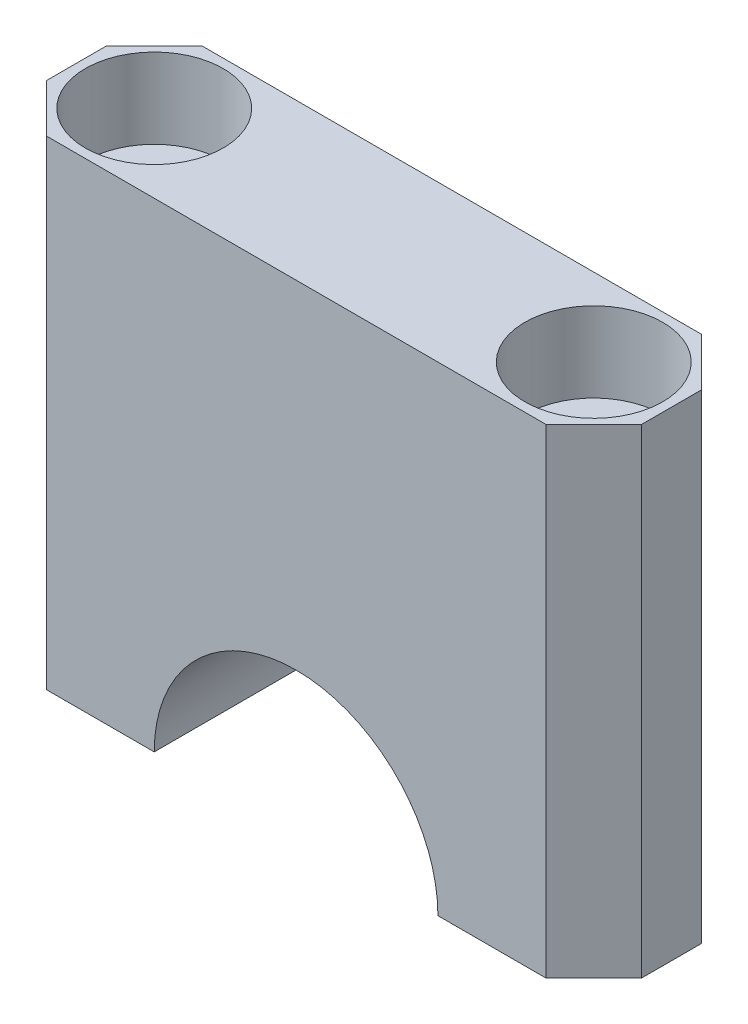
SolidWorks part; units mm, degrees
material "ABS"
ref_plane "Płaszczyzna przednia" through (0, 0, 0) normal (0, 0, 1) x (1, 0, 0)
ref_plane "Płaszczyzna górna" through (0, 0, 0) normal (0, 1, 0) x (1, 0, 0)
ref_plane "Płaszczyzna prawa" through (0, 0, 0) normal (1, 0, 0) x (0, 0, -1)
sketch "Szkic1" plane through (0, 0, 0) normal (0, 1, 0) x (1, 0, 0)
  line L0 (0, -3.9) -> (0, 3.9) construction
  line L1 (12.5, 3.9) -> (-12.5, 3.9)
  line L2 (14.9, 0) -> (-14.9, 0) construction
  line L3 (-14.9, -1.5) -> (-14.9, 1.5)
  line L4 (-14.9, 1.5) -> (-12.5, 3.9)
  line L5 (14.9, 1.5) -> (14.9, -1.5)
  line L6 (14.9, 1.5) -> (12.5, 3.9)
  line L7 (-14.9, -1.5) -> (-12.5, -3.9)
  line L8 (12.5, -3.9) -> (-12.5, -3.9)
  line L9 (14.9, -1.5) -> (12.5, -3.9)
  line L10 (0, 0) -> (-11, 0) construction
  circle A0 centre (-11, 0) radius 2.1
  circle A1 centre (11, 0) radius 2.1
  point P4 (0, 0)
  point P9 (0, 3.9)
  point P12 (0, 0)
  point P15 (-14.9, 0)
  point P18 (14.9, 0)
  dimension "D7" = 4.2
  dimension "D1" = 7.8
  dimension "D2" = 29.8
  dimension "D3" = 3
  dimension "D4" = 25
  dimension "D5" = 3
  dimension "D6" = 11
extrude "Dodanie-wyciągnięcie1" add sketch "Szkic1" against normal blind 24
ref_plane "Płaszczyzna1" through (0, 0, -3.9) normal (0, 0, -1) x (-1, 0, 0)
sketch "Szkic2" plane through (0, 0, -3.9) normal (0, 0, -1) x (-1, 0, 0)
  line L0 (0, 0) -> (0, -24) construction
  line L1 (-12.5, -24) -> (12.5, -24) construction
  line L2 (-7.1, -24) -> (7.1, -24)
  arc A0 (7.1, -24) -> (-7.1, -24) centre (0, -24) ccw
  dimension "D2" = 7.1
  dimension "D1" = 24
extrude "Wytnij-wyciągnięcie1" cut sketch "Szkic2" against normal up to next
sketch "Szkic3" plane through (0, 0, 0) normal (0, 1, 0) x (1, 0, 0)
  line L0 (0, -4.29) -> (0, 4.29) construction
  circle A0 centre (-11, 0) radius 3.45
  circle A1 centre (11, 0) radius 3.45
  dimension "D1" = 6.9
extrude "Wytnij-wyciągnięcie2" cut sketch "Szkic3" against normal blind 4
equation "\"Tolerance\"= 0.1"
equation "\"Depth\"=10"
equation "\"D1@Szkic1\"=\"RailZ\"-\"Tolerance\"*2"
equation "\"Width\"= 16"
equation "\"D2@Szkic1\"=\"Diameter\"+\"RailX\"*2-\"Tolerance\"*2"
equation "\"Diameter\"= 14"
equation "\"RailX\"= 8"
equation "\"RailZ\"= 8"
equation "\"D3@Szkic1\"=\"RailZ\"*0.4-\"Tolerance\"*2"
equation "\"D4@Szkic1\"=\"Diameter\"+2*0.7*\"RailX\"-\"Tolerance\"*2"
equation "\"D5@Szkic1\"=\"RailZ\"*0.4-\"Tolerance\"*2"
equation "\"D6@Szkic1\"=\"Diameter\"/2+\"RailX\"/2"
equation "\"Hight\"=24"
equation "\"D1@Szkic2\"=\"Hight\""
equation "\"D2@Szkic2\"=\"Diameter\"/2+\"Tolerance\""
equation "\"D1@Dodanie-wyciągnięcie1\"=\"Hight\""
